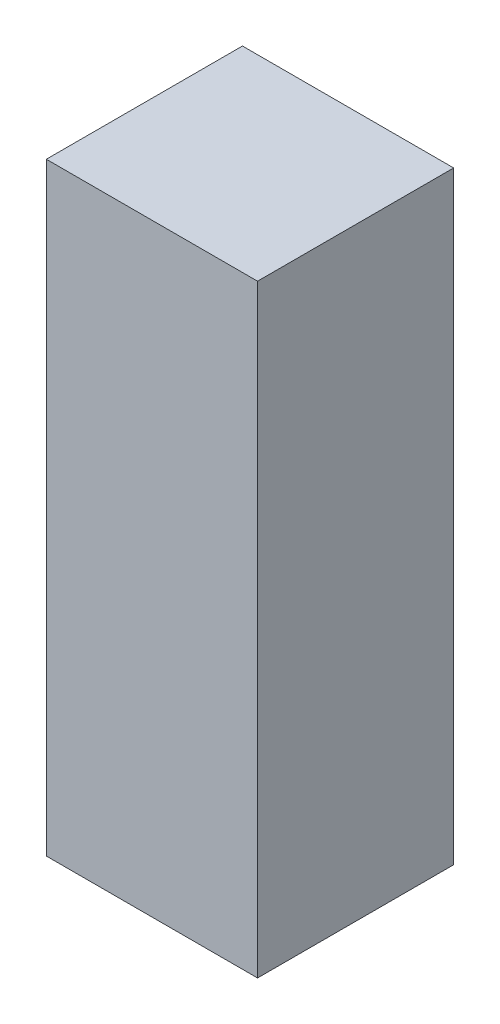
SolidWorks part; units mm, degrees
ref_plane "Front Plane" through (0, 0, 0) normal (0, 0, 1) x (1, 0, 0)
ref_plane "Top Plane" through (0, 0, 0) normal (0, 1, 0) x (1, 0, 0)
ref_plane "Right Plane" through (0, 0, 0) normal (1, 0, 0) x (0, 0, -1)
other "Configuration Table"
sketch "Sketch1" plane through (0, 0, 0) normal (0, 0, 1) x (1, 0, 0)
  line L1 (24, 1700) -> (38, 1700)
  line L2 (24, 1700) -> (24, 1740)
  line L3 (24, 1740) -> (38, 1740)
  line L4 (38, 1700) -> (38, 1740)
extrude "PRESS_kova_kapagi_mentese_2_1" add sketch "Sketch1" along normal blind 13 from offset 20 separate body
